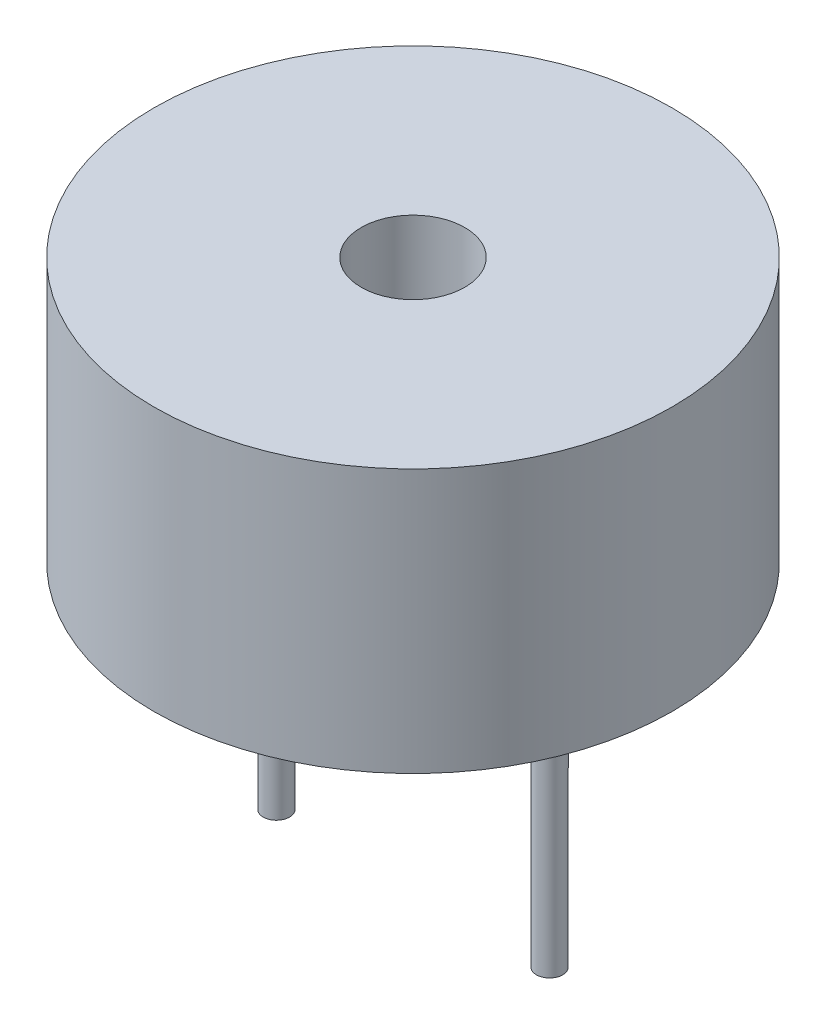
SolidWorks part; units mm, degrees
ref_plane "Front Plane" through (0, 0, 0) normal (0, 0, 1) x (1, 0, 0)
ref_plane "Top Plane" through (0, 0, 0) normal (0, 1, 0) x (1, 0, 0)
ref_plane "Right Plane" through (0, 0, 0) normal (1, 0, 0) x (0, 0, -1)
sketch "Sketch2" plane through (0, 0, 0) normal (0, 1, 0) x (1, 0, 0)
  circle A0 centre (0, 0) radius 6.985
  dimension "D1" = 13.97
extrude "Extrude1" add sketch "Sketch2" along normal blind 7.112
sketch "Sketch3" plane through (0, 0, 0) normal (0, -1, 0) x (1, 0, 0)
  line L0 (-3.683, 0) -> (3.683, 0) construction
  circle A0 centre (3.683, 0) radius 0.3556
  circle A1 centre (-3.683, 0) radius 0.3556
  dimension "D2" = 0.7112
  dimension "D1" = 7.366
extrude "Extrude2" add sketch "Sketch3" along normal blind 7.62
sketch "Sketch4" plane through (0, 7.112, 0) normal (0, 1, 0) x (1, 0, 0)
  circle A0 centre (0, 0) radius 1.397
  dimension "D1" = 2.794
extrude "Extrude3" cut sketch "Sketch4" against normal blind 3.81
